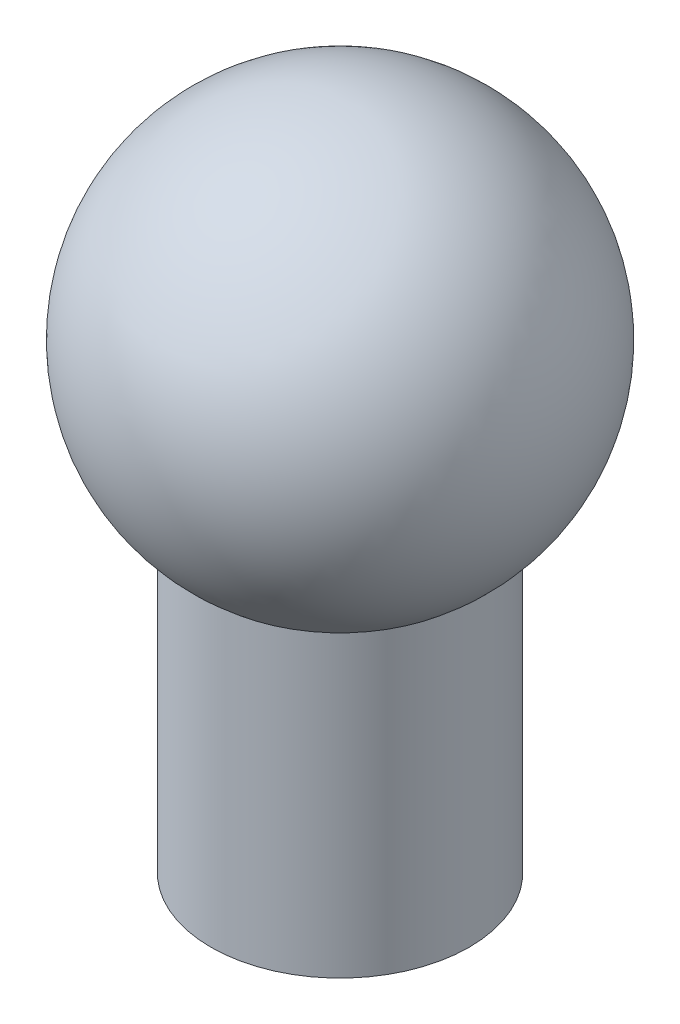
SolidWorks part; units mm, degrees
ref_plane "前视基准面" through (0, 0, 0) normal (0, 0, 1) x (1, 0, 0)
ref_plane "上视基准面" through (0, 0, 0) normal (0, 1, 0) x (1, 0, 0)
ref_plane "右视基准面" through (0, 0, 0) normal (1, 0, 0) x (0, 0, -1)
sketch "草图1" plane through (0, 0, 0) normal (0, 1, 0) x (1, 0, 0)
  circle A0 centre (0, 0) radius 2.8
extrude "凸台-拉伸1" add sketch "草图1" along normal blind 10
sketch "草图2" plane through (0, 10, 0) normal (0, 1, 0) x (1, 0, 0)
  line L0 (0, 4.5) -> (0, -4.5)
  arc A0 (0, -4.5) -> (0, 4.5) centre (0, 0) ccw
revolve "旋转1" add sketch "草图2" angle 360 about L0
